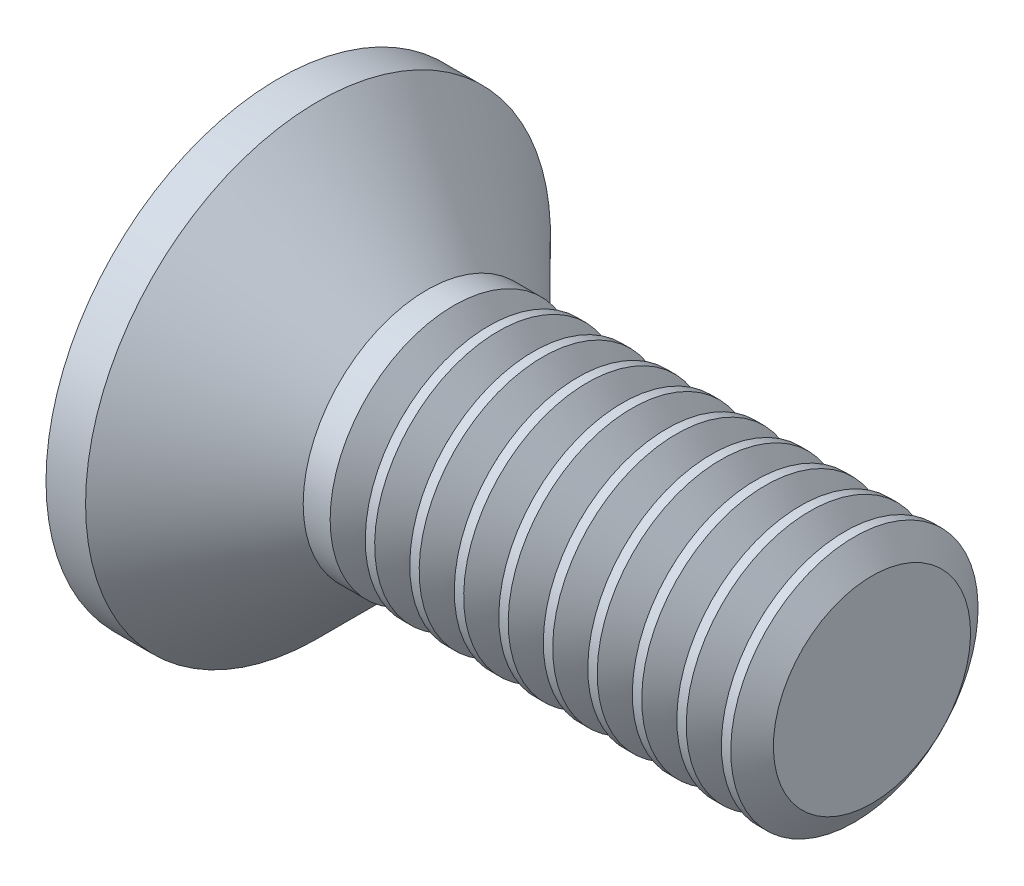
SolidWorks part; units mm, degrees
revolve "Base-Revolve" add sketch "BodySke" angle 360 about L5
sketch "BodySke" plane through (0, 0, 0) normal (0, 0, 1) x (1, 0, 0)
  line L0 (0, 0) -> (0, 2.35)
  line L1 (0, 2.35) -> (0.4, 2.35)
  line L2 (1.5, 1.25) -> (6, 1.25)
  line L3 (6, 1.25) -> (6, 0)
  line L4 (6, 0) -> (0, 0)
  line L5 (-6.35, 0) -> (82.55, 0) construction
  line L6 (1.5, -1.25) -> (6, -1.25) construction
  line L7 (0.4, -2.35) -> (1.5, -1.25) construction
  line L8 (0.4, 2.35) -> (1.5, 1.25)
  line L9 (0, -2.35) -> (0.4, -2.35) construction
  line L10 (1.95, 2.8375) -> (1.95, -6.6875) construction
  line L11 (0, 6.35) -> (0, -3.175) construction
  dimension "Diameter" = 2.5
  dimension "Length" = 6
  dimension "Head_ht" = 1.5
  dimension "Head_dia" = 4.7
  dimension "Head_ang" = 90
  dimension "D6" = 0.4
  dimension "Advance" = 0.45
  dimension "Thread_nom" = 6
cosmetic thread "ThreadCosmetic" [suppressed] parameters "Thread_length"=4.05, "Thread_minor"=1.993
extrude "Slot" [suppressed] cut sketch "Sketch2" against normal blind 0.7
sketch "Sketch2" plane through (0, 0, 0) normal (-1, 0, 0) x (0, 0, 1)
  line L0 (-2.35, -0.4) -> (2.35, -0.4)
  line L1 (-2.35, -0.4) -> (-2.35, 0.4)
  line L2 (2.35, 0.4) -> (-2.35, 0.4)
  line L3 (2.35, 0.4) -> (2.35, -0.4)
  dimension "Slot_width" = 0.8
  dimension "D1" = 0.4
  dimension "D2" = 4.7
  dimension "D3" = 2.35
ref_plane "Plane1" through (0, 0, 0) normal (0, 0, 1) x (1, 0, 0)
ref_plane "Plane2" through (0, 0, 0) normal (0, 1, 0) x (1, 0, 0)
ref_plane "Plane3" through (0, 0, 0) normal (1, 0, 0) x (0, 0, -1)
sketch "Sketch3" plane through (0, 0, 0) normal (-1, 0, 0) x (0, 0, 1)
  line L0 (-0.37, 1.4) -> (0.37, 1.4)
  line L1 (0.37, 1.4) -> (0.37, -1.4)
  line L2 (0.37, -1.4) -> (-0.37, -1.4)
  line L3 (-0.37, -1.4) -> (-0.37, 1.4)
  dimension "Cross_dia" = 2.8
  dimension "Cross_width" = 0.74
  dimension "D1" = 1.4
  dimension "D2" = 0.37
ref_plane "Plane4" through (1.78, 0, 0) normal (-1, 0, 0) x (0, 0, 1)
sketch "Sketch4" plane through (1.78, 0, 0) normal (-1, 0, 0) x (0, 0, 1)
  line L0 (-0.185, 0.185) -> (0.185, 0.185)
  line L3 (0.185, 0.185) -> (0.185, -0.185)
  line L4 (0.185, -0.185) -> (-0.185, -0.185)
  line L5 (-0.185, -0.185) -> (-0.185, 0.185)
  dimension "D2" = 0.37
  dimension "D1" = 0.37
  dimension "D3" = 0.185
  dimension "D4" = 0.185
loft "Cross" cut profiles "Sketch3", "Sketch4"
pattern_circular "CirPattern1" count 2 every 90 about axis through (0, 0, 0) along (1, 0, 0) of "Cross"
sketch "ThdSchSke" plane through (0, 0, 0) normal (0, 0, 1) x (1, 0, 0)
  line L0 (1.95, -0.9965) -> (1.7725, -1.25)
  line L1 (1.95, -0.9965) -> (2.1275, -1.25)
  line L2 (2.1275, -1.25) -> (2.1275, -1.5625)
  line L3 (-3.175, 0) -> (5.1513, 0) construction
  line L5 (2.1275, -1.5625) -> (1.7725, -1.5625)
  line L6 (1.7725, -1.5625) -> (1.7725, -1.25)
  line L7 (0, 2.35) -> (0, -2.35) construction
  dimension "Diameter" = 2.5
  dimension "Thread_minor" = 1.993
  dimension "Start" = 1.95
revolve "ThreadSchematic" cut sketch "ThdSchSke" angle 360 about L3
pattern_linear "ThdSchPat" count 10 spacing 0.45 along (1, 0, 0) of "ThreadSchematic"
equation "\"D1@Sketch3\" = \"Cross_dia@Sketch3\" / 2"
equation "\"D2@Sketch3\" = \"Cross_width@Sketch3\" / 2"
equation "\"D1@Sketch4\" = \"Cross_width@Sketch3\" *.5"
equation "\"D2@Sketch4\" = \"D1@Sketch4\""
equation "\"D4@Sketch4\" = \"D2@Sketch4\" / 2"
equation "\"D3@Sketch4\" = \"D1@Sketch4\" / 2"
equation "\"D1@Sketch2\" = \"Slot_width@Sketch2\" / 2"
equation "\"D2@Sketch2\" = \"Head_dia@BodySke\""
equation "\"D3@Sketch2\" = \"D2@Sketch2\" / 2"
equation "\"Thread_length@ThreadCosmetic\" = ((sgn( (\"Length@BodySke\" - \"Advance@BodySke\" - \"Head_ht@BodySke\" ) - \"Thread_nom@BodySke\" )-1)*( (\"Length@BodySke\" - \"Advance@BodySke\" - \"Head_ht@BodySke\" ) - \"Thread_nom@BodySke\" ))/-2+ \"Thread_nom@BodySke\""
equation "\"Thread_minor@ThdSchSke\" = \"Thread_minor@ThreadCosmetic\""
equation "\"Diameter@ThdSchSke\" = \"Diameter@BodySke\""
equation "\"Overcut@ThdSchSke\" = \"Diameter@BodySke\" * 1.25"
equation "\"Start@ThdSchSke\" = 0.000001 + \"Length@BodySke\" - \"Thread_length@ThreadCosmetic\"  '---Countersunk---"
equation "\"Num_threads@ThdSchPat\" = int( \"Thread_length@ThreadCosmetic\" / \"Advance@BodySke\" + 0.999 )  + 1"
equation "\"Advance@ThdSchPat\" = \"Thread_length@ThreadCosmetic\" /  (\"Num_threads@ThdSchPat\" - 1) 'relax it"
